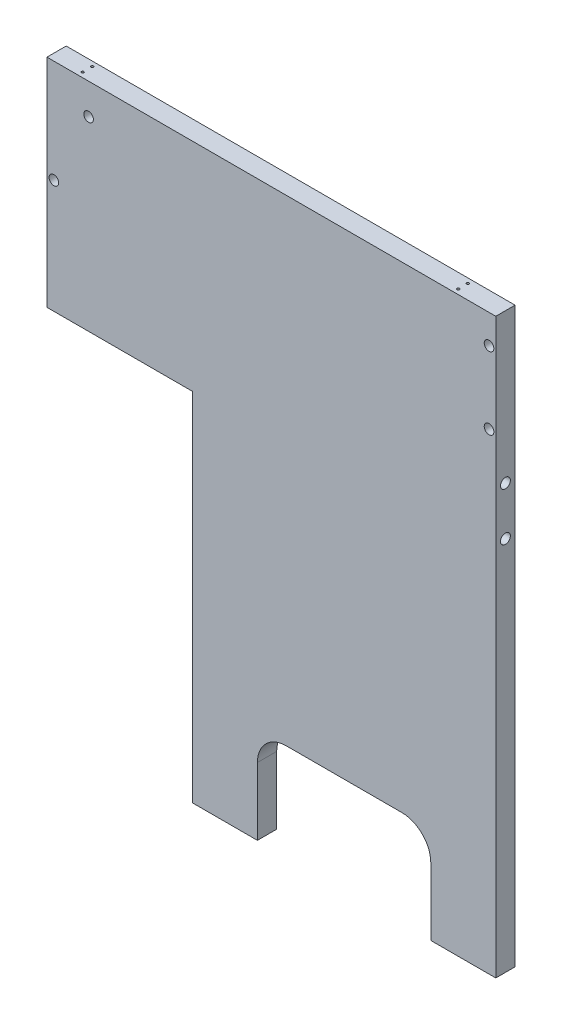
SolidWorks part; units mm, degrees
ref_plane "前视基准面" through (0, 0, 0) normal (0, 0, 1) x (1, 0, 0)
ref_plane "上视基准面" through (0, 0, 0) normal (0, 1, 0) x (1, 0, 0)
ref_plane "右视基准面" through (0, 0, 0) normal (1, 0, 0) x (0, 0, -1)
sketch "草图1" plane through (0, 0, 0) normal (0, 0, 1) x (1, 0, 0)
  line L0 (0, 0) -> (466, 0)
  line L1 (466, 0) -> (466, -595)
  line L2 (466, -595) -> (151, -595)
  line L3 (151, -595) -> (151, -225)
  line L4 (151, -225) -> (0, -225)
  line L5 (0, -225) -> (0, 0)
  dimension "D1" = 466
  dimension "D2" = 595
  dimension "D3" = 315
  dimension "D4" = 225
extrude "凸台-拉伸1" add sketch "草图1" against normal blind 20
sketch "草图2" plane through (0, 0, 0) normal (0, 0, 1) x (1, 0, 0)
  line L0 (218.5, -595) -> (218.5, -525)
  line L1 (151, -595) -> (466, -595) construction
  line L2 (248.5, -495) -> (368.5, -495)
  line L3 (398.5, -525) -> (398.5, -595)
  line L4 (398.5, -595) -> (218.5, -595)
  line L5 (466, -595) -> (466, 0) construction
  line L7 (0, 0) -> (0, -225) construction
  line L8 (466, 0) -> (0, 0) construction
  arc A0 (368.5, -495) -> (398.5, -525) centre (368.5, -525) cw
  arc A1 (218.5, -525) -> (248.5, -495) centre (248.5, -525) cw
  circle A2 centre (43.2, -32) radius 5
  circle A3 centre (459, -30) radius 5
  circle A4 centre (459, -105) radius 5
  circle A5 centre (7.2, -107) radius 5
  dimension "D1" = 30
  dimension "D5" = 43.2
  dimension "D6" = 36
  dimension "D7" = 10
  dimension "D8" = 10
  dimension "D9" = 75
  dimension "D10" = 32
  dimension "D11" = 2
  dimension "D12" = 75
  dimension "D13" = 10
  dimension "D14" = 10
  dimension "D15" = 415.8
  dimension "D2" = 180
  dimension "D3" = 100
  dimension "D4" = 67.5
extrude "切除-拉伸1" cut sketch "草图2" against normal through all
sketch "草图3" plane through (0, 0, 0) normal (-1, 0, 0) x (0, 0, 1)
  line L0 (-20, 0) -> (-20, -225) construction
  line L1 (-20, 0) -> (0, 0) construction
  circle A0 centre (-10, -155) radius 5.15
  circle A1 centre (-10, -205) radius 5.15
  point P9 (-10, 0)
  dimension "D1" = 10
  dimension "D2" = 10.3
  dimension "D3" = 10.3
  dimension "D4" = 50
  dimension "D5" = 155
extrude "切除-拉伸2" cut sketch "草图3" against normal blind 20
sketch "草图4" plane through (466, 0, 0) normal (1, 0, 0) x (0, 0, -1)
  line L0 (20, 0) -> (0, 0) construction
  line L1 (0, -595) -> (0, 0) construction
  circle A0 centre (10, -155) radius 5.15
  circle A1 centre (10, -205) radius 5.15
  dimension "D1" = 50
  dimension "D2" = 155
  dimension "D3" = 10.3
  dimension "D4" = 10.3
  dimension "D5" = 10
extrude "切除-拉伸3" cut sketch "草图4" against normal blind 20
sketch "草图5" plane through (0, 0, 0) normal (0, 1, 0) x (1, 0, 0)
  line L0 (466, 20) -> (0, 20) construction
  line L2 (0, 20) -> (0, 0) construction
  circle A0 centre (32, 15) radius 1.25
  circle A1 centre (32, 5) radius 1.25
  circle A2 centre (422, 15) radius 1.25
  circle A3 centre (422, 5) radius 1.25
  point P12 (0, 0)
  point P13 (0, 0)
  point P14 (0, 0)
  dimension "D1" = 2.5
  dimension "D2" = 2.5
  dimension "D3" = 10
  dimension "D4" = 5
  dimension "D5" = 32
  dimension "D6" = 2.5
  dimension "D7" = 2.5
  dimension "D8" = 390
extrude "切除-拉伸4" cut sketch "草图5" against normal blind 10
